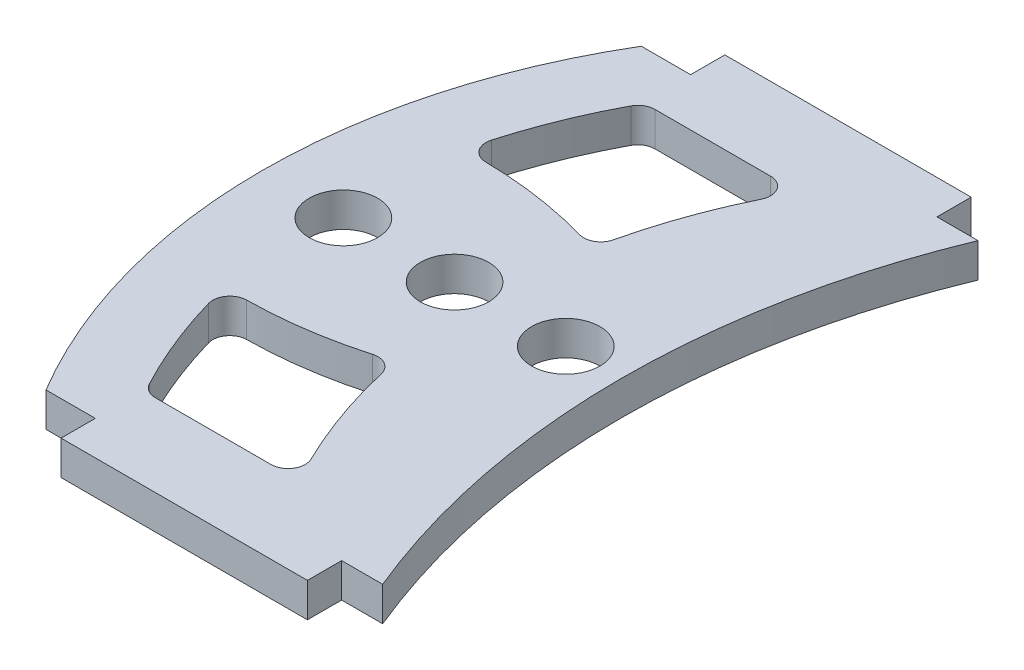
SolidWorks part; units mm, degrees
ref_plane "Front Plane" through (0, 0, 0) normal (0, 0, 1) x (1, 0, 0)
ref_plane "Top Plane" through (0, 0, 0) normal (0, 1, 0) x (1, 0, 0)
ref_plane "Right Plane" through (0, 0, 0) normal (1, 0, 0) x (0, 0, -1)
sketch "Sketch1" plane through (0, 0, 0) normal (0, 1, 0) x (1, 0, 0)
  line L0 (7.9614, 38.3984) -> (10.8429, 38.3984)
  line L1 (10.8429, 38.3984) -> (10.8429, 40.3984)
  line L2 (10.8429, 40.3984) -> (25.2429, 40.3984)
  line L3 (25.2429, 40.3984) -> (25.2429, 38.3984)
  line L4 (25.2429, 38.3984) -> (27.643, 38.3984)
  line L5 (27.643, 3.5984) -> (25.2429, 3.5984)
  line L6 (25.2429, 3.5984) -> (25.2429, 1.5984)
  line L7 (25.2429, 1.5984) -> (10.8429, 1.5984)
  line L8 (10.8429, 1.5984) -> (10.8429, 3.5984)
  line L9 (10.8429, 3.5984) -> (7.9614, 3.5984)
  line L10 (11.5584, 6.3984) -> (18.3142, 6.3984)
  line L11 (11.5584, 35.5984) -> (18.3142, 35.5984)
  circle A0 centre (14.4452, 20.9984) radius 2
  circle A1 centre (7.9452, 20.9984) radius 2
  circle A2 centre (20.9452, 20.9984) radius 2
  arc A3 (27.643, 38.3984) -> (27.643, 3.5984) centre (69.7927, 20.9984) ccw
  arc A4 (7.9614, 38.3984) -> (7.9614, 3.5984) centre (37.1717, 20.9984) ccw
  arc A5 (10.6752, 6.9294) -> (11.5584, 6.3984) centre (11.5584, 7.3984) ccw
  arc A6 (18.3142, 6.3984) -> (19.2128, 7.8371) centre (18.3142, 7.3984) ccw
  arc A7 (16.9499, 14.2096) -> (19.2128, 7.8371) centre (46.1717, 20.9984) ccw
  arc A8 (16.9499, 14.2096) -> (15.7022, 14.9451) centre (15.9758, 13.9833) ccw
  arc A9 (9.2816, 14.0117) -> (15.7022, 14.9451) centre (8.9998, 38.4992) ccw
  arc A10 (9.2816, 14.0117) -> (8.3318, 12.7364) centre (9.2931, 13.0118) ccw
  arc A11 (8.3318, 12.7364) -> (10.6752, 6.9294) centre (37.1717, 20.9984) ccw
  arc A12 (11.5584, 35.5984) -> (10.6752, 35.0673) centre (11.5584, 34.5984) ccw
  arc A13 (19.2128, 34.1596) -> (18.3142, 35.5984) centre (18.3142, 34.5984) ccw
  arc A14 (19.2128, 34.1596) -> (16.9499, 27.7871) centre (46.1717, 20.9984) ccw
  arc A15 (15.7022, 27.0516) -> (16.9499, 27.7871) centre (15.9758, 28.0134) ccw
  arc A16 (15.7022, 27.0516) -> (9.2816, 27.985) centre (8.9998, 3.4975) ccw
  arc A17 (8.3318, 29.2604) -> (9.2816, 27.985) centre (9.2931, 28.985) ccw
  arc A18 (10.6752, 35.0673) -> (8.3318, 29.2604) centre (37.1717, 20.9984) ccw
sketch "Sketch2" plane through (0, 0, 0) normal (0, 1, 0) x (1, 0, 0)
  line L0 (7.9614, 38.3984) -> (10.8429, 38.3984)
  line L1 (10.8429, 38.3984) -> (10.8429, 40.3984)
  line L2 (10.8429, 40.3984) -> (25.2429, 40.3984)
  line L3 (25.2429, 40.3984) -> (25.2429, 38.3984)
  line L4 (25.2429, 38.3984) -> (27.643, 38.3984)
  line L5 (27.643, 3.5984) -> (25.2429, 3.5984)
  line L6 (25.2429, 3.5984) -> (25.2429, 1.5984)
  line L7 (25.2429, 1.5984) -> (10.8429, 1.5984)
  line L8 (10.8429, 1.5984) -> (10.8429, 3.5984)
  line L9 (10.8429, 3.5984) -> (7.9614, 3.5984)
  line L10 (11.5584, 6.3984) -> (18.3142, 6.3984)
  line L11 (11.5584, 35.5984) -> (18.3142, 35.5984)
  circle A0 centre (14.4452, 20.9984) radius 2
  circle A1 centre (7.9452, 20.9984) radius 2
  circle A2 centre (20.9452, 20.9984) radius 2
  arc A3 (27.643, 38.3984) -> (27.643, 3.5984) centre (69.7927, 20.9984) ccw
  arc A4 (7.9614, 38.3984) -> (7.9614, 3.5984) centre (37.1717, 20.9984) ccw
  arc A5 (10.6752, 6.9294) -> (11.5584, 6.3984) centre (11.5584, 7.3984) ccw
  arc A6 (18.3142, 6.3984) -> (19.2128, 7.8371) centre (18.3142, 7.3984) ccw
  arc A7 (16.9499, 14.2096) -> (19.2128, 7.8371) centre (46.1717, 20.9984) ccw
  arc A8 (16.9499, 14.2096) -> (15.7022, 14.9451) centre (15.9758, 13.9833) ccw
  arc A9 (9.2816, 14.0117) -> (15.7022, 14.9451) centre (8.9998, 38.4992) ccw
  arc A10 (9.2816, 14.0117) -> (8.3318, 12.7364) centre (9.2931, 13.0118) ccw
  arc A11 (8.3318, 12.7364) -> (10.6752, 6.9294) centre (37.1717, 20.9984) ccw
  arc A12 (11.5584, 35.5984) -> (10.6752, 35.0673) centre (11.5584, 34.5984) ccw
  arc A13 (19.2128, 34.1596) -> (18.3142, 35.5984) centre (18.3142, 34.5984) ccw
  arc A14 (19.2128, 34.1596) -> (16.9499, 27.7871) centre (46.1717, 20.9984) ccw
  arc A15 (15.7022, 27.0516) -> (16.9499, 27.7871) centre (15.9758, 28.0134) ccw
  arc A16 (15.7022, 27.0516) -> (9.2816, 27.985) centre (8.9998, 3.4975) ccw
  arc A17 (8.3318, 29.2604) -> (9.2816, 27.985) centre (9.2931, 28.985) ccw
  arc A18 (10.6752, 35.0673) -> (8.3318, 29.2604) centre (37.1717, 20.9984) ccw
extrude "Boss-Extrude1" add sketch "Sketch2" along normal blind 2
